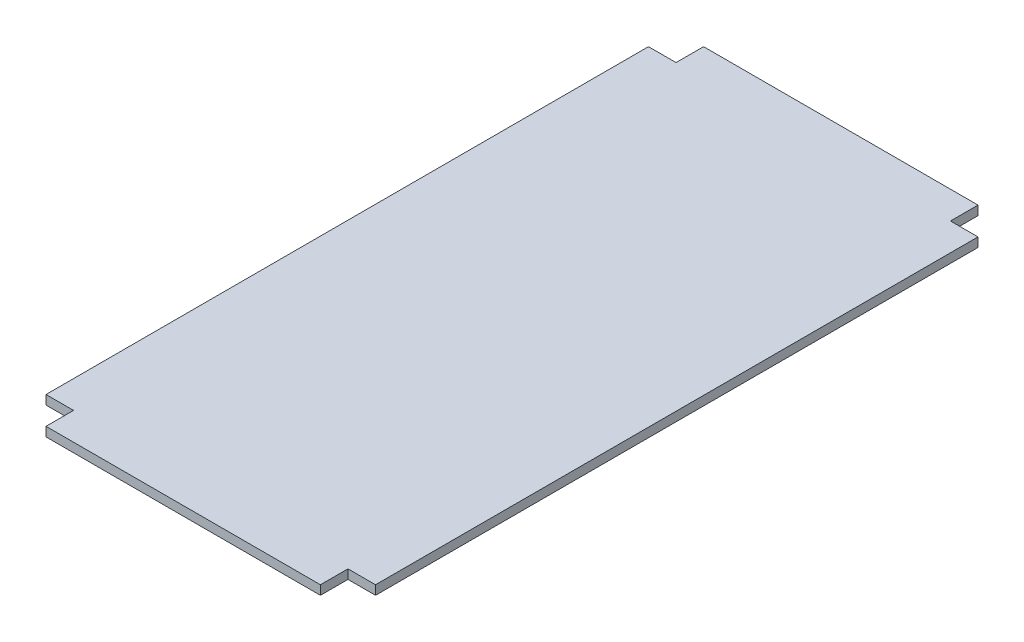
SolidWorks part; units mm, degrees
ref_plane "Front Plane" through (0, 0, 0) normal (0, 0, 1) x (1, 0, 0)
ref_plane "Top Plane" through (0, 0, 0) normal (0, 1, 0) x (1, 0, 0)
ref_plane "Right Plane" through (0, 0, 0) normal (1, 0, 0) x (0, 0, -1)
sketch "Sketch1" plane through (0, 0, 0) normal (0, 1, 0) x (1, 0, 0)
  line L1 (0, 0) -> (227.838, 0)
  line L2 (0, 0) -> (0, 454.66)
  line L3 (0, 454.66) -> (227.838, 454.66)
  line L4 (227.838, 0) -> (227.838, 454.66)
  dimension "D1" = 227.838
  dimension "D2" = 454.66
extrude "Boss-Extrude1" add sketch "Sketch1" along normal blind 6.35
sketch "Sketch2" plane through (0, 6.35, 0) normal (0, 1, 0) x (1, 0, 0)
  line L0 (0, 0) -> (227.838, 0) construction
  line L1 (0, 0) -> (19.05, 0)
  line L2 (0, 0) -> (0, 19.05)
  line L3 (0, 19.05) -> (19.05, 19.05)
  line L4 (19.05, 0) -> (19.05, 19.05)
  line L5 (0, 454.66) -> (19.05, 454.66)
  line L6 (0, 454.66) -> (0, 435.61)
  line L7 (0, 435.61) -> (19.05, 435.61)
  line L8 (19.05, 454.66) -> (19.05, 435.61)
  line L9 (227.838, 454.66) -> (208.788, 454.66)
  line L10 (227.838, 454.66) -> (227.838, 435.61)
  line L11 (227.838, 435.61) -> (208.788, 435.61)
  line L12 (208.788, 454.66) -> (208.788, 435.61)
  line L13 (227.838, 0) -> (208.788, 0)
  line L14 (227.838, 0) -> (227.838, 19.05)
  line L15 (227.838, 19.05) -> (208.788, 19.05)
  line L16 (208.788, 0) -> (208.788, 19.05)
  line L17 (227.838, 0) -> (227.838, 454.66) construction
  dimension "D1" = 19.05
  dimension "D2" = 19.05
  dimension "D3" = 19.05
  dimension "D4" = 19.05
  dimension "D5" = 19.05
  dimension "D6" = 19.05
  dimension "D7" = 19.05
  dimension "D8" = 19.05
extrude "Cut-Extrude1" cut sketch "Sketch2" against normal through all
